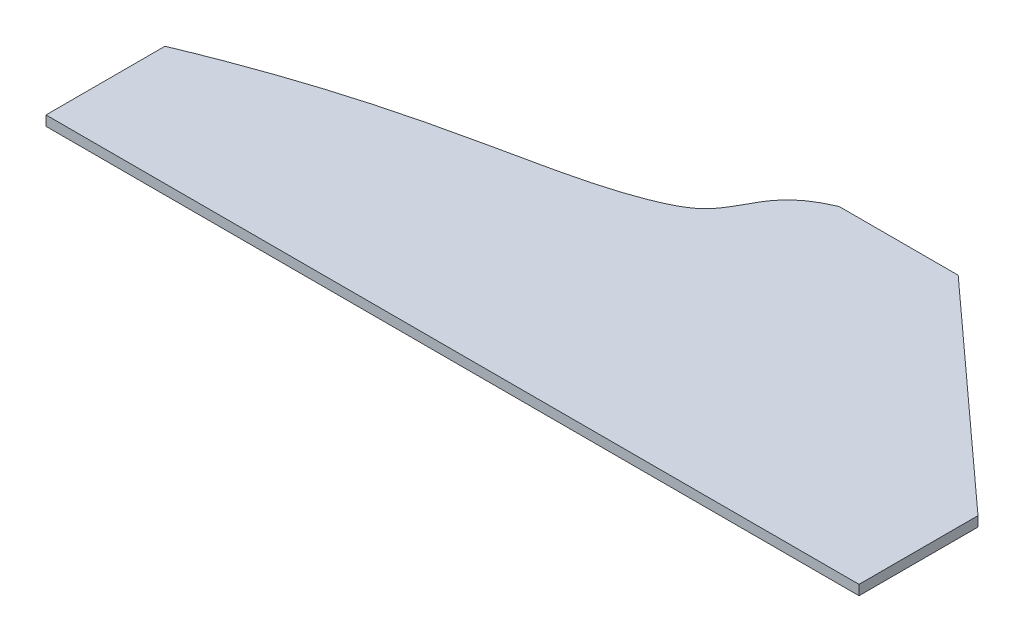
SolidWorks part; units mm, degrees
material "Plain Carbon Steel"
ref_plane "Front Plane" through (0, 0, 0) normal (0, 0, 1) x (1, 0, 0)
ref_plane "Top Plane" through (0, 0, 0) normal (0, 1, 0) x (1, 0, 0)
ref_plane "Right Plane" through (0, 0, 0) normal (1, 0, 0) x (0, 0, -1)
sketch "Sketch1" plane through (0, 0, 0) normal (0, 1, 0) x (1, 0, 0)
  line L0 (0, 0) -> (0, 180.0537) construction
  line L1 (-222.25, 0) -> (107.95, 0) construction
  line L2 (-57.15, 0) -> (-57.15, 342.9) construction
  line L3 (-152.4, 0) -> (107.95, 0)
  line L4 (107.95, 0) -> (107.95, 38.1)
  line L5 (0, 101.6) -> (38.1, 101.6)
  line L6 (38.1, 101.6) -> (107.95, 38.1)
  line L7 (-152.4, 0) -> (-152.4, 38.1)
  line L8 (-158.75, -38.1) -> (44.45, -38.1) construction
  line L9 (-25.4, 342.9) -> (-25.4, 76.2) construction
  line L10 (-25.4, 76.2) -> (-88.9, 76.2) construction
  line L11 (-88.9, 76.2) -> (-88.9, 342.9) construction
  line L12 (-88.9, 342.9) -> (-25.4, 342.9) construction
  line L13 (6.8112, 104.438) -> (-16.1405, 94.8748) construction
  line L14 (-152.4, 38.1) -> (0, 101.6) construction
  line L15 (-107.9277, 56.6301) -> (-173.7203, 29.2165) construction
  spline S0 degree 3 poles (-152.4, 38.1) (-93.526, 62.6308) (-55.6327, 62.2445) (-13.2352, 81.3413) (-16.3127, 94.803) (0, 101.6) knots 0 0 0 0 0.617418 0.717418 1 1 1 1
  dimension "D7" = 38.1
  dimension "D1" = 57.15
  dimension "D2" = 330.2
  dimension "D3" = 38.1
  dimension "D4" = 381
  dimension "D5" = 266.7
  dimension "D6" = 63.5
  dimension "D8" = 101.6
  dimension "D9" = 38.1
  dimension "D10" = 152.4
extrude "Boss-Extrude1" add sketch "Sketch1" along normal blind 3.175
